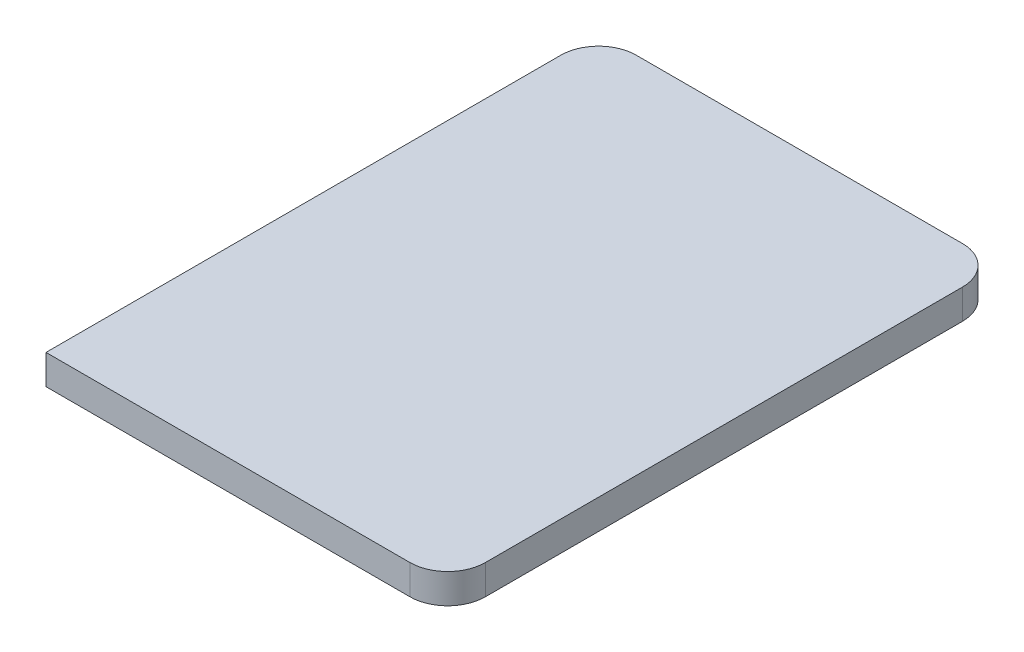
SolidWorks part; units mm, degrees
ref_plane "Front Plane" through (0, 0, 0) normal (0, 0, 1) x (1, 0, 0)
ref_plane "Top Plane" through (0, 0, 0) normal (0, 1, 0) x (1, 0, 0)
ref_plane "Right Plane" through (0, 0, 0) normal (1, 0, 0) x (0, 0, -1)
sketch "Sketch2" plane through (0, 0, 0) normal (0, 1, 0) x (1, 0, 0)
  line L0 (0, 2) -> (0, 0)
  line L1 (2, 0) -> (19.3, 0)
  line L2 (0, 2) -> (0, 27.3)
  line L3 (2, 29.3) -> (19.3, 29.3)
  line L4 (21.3, 2) -> (21.3, 27.3)
  line L5 (0, 0) -> (2, 0)
  arc A0 (19.3, 0) -> (21.3, 2) centre (19.3, 2) ccw
  arc A1 (0, 27.3) -> (2, 29.3) centre (2, 27.3) cw
  arc A2 (19.3, 29.3) -> (21.3, 27.3) centre (19.3, 27.3) cw
  point P7 (21.3, 0)
  point P10 (0, 29.3)
  point P13 (21.3, 29.3)
  point P16 (0, 0)
  dimension "D3" = 2
  dimension "D4" = 2
  dimension "D5" = 2
  dimension "D1" = 21.3
  dimension "D2" = 29.3
extrude "Boss-Extrude2" add sketch "Sketch2" along normal blind 1.575
equation "\"M1PCB_side\"= 10mm"
equation "\"ODRM_TC203\"= 10.650mm"
equation "\"IDRM_TC203\"= 5.5mm"
equation "\"HTM_TC203\"= 7.620mm"
equation "\"D1@Sketch2\"=\"ODRM_TC203\"*2"
equation "\"D2@Sketch2\"=(\"ODRM_TC203\"*2)+8mm"
